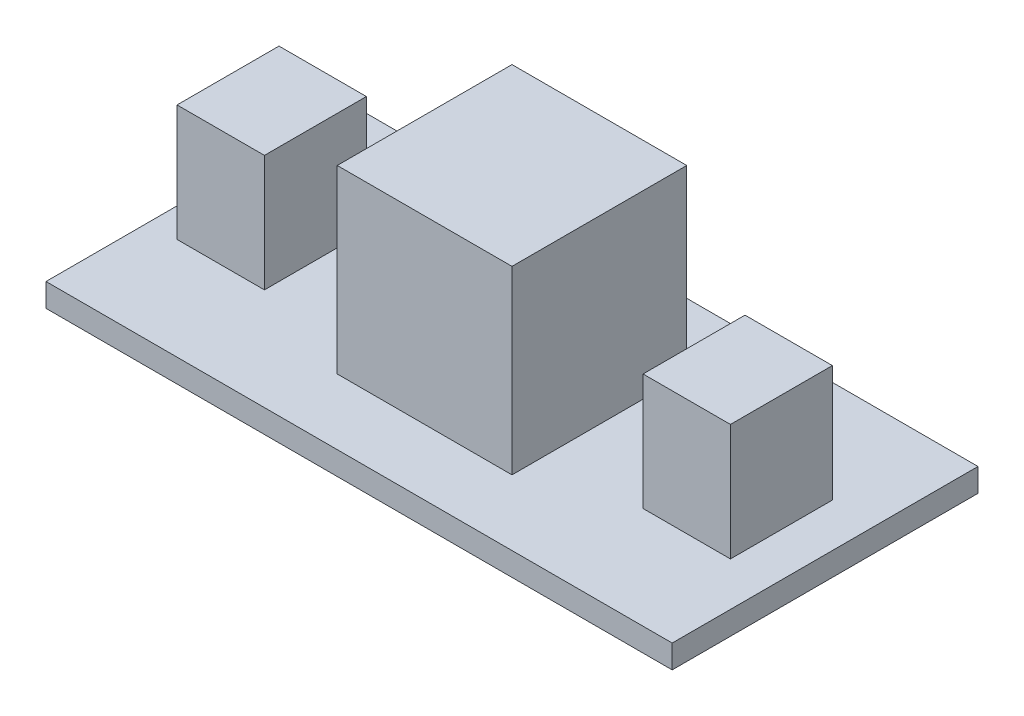
SolidWorks part; units mm, degrees
ref_plane "Front Plane" through (0, 0, 0) normal (0, 0, 1) x (1, 0, 0)
ref_plane "Top Plane" through (0, 0, 0) normal (0, 1, 0) x (1, 0, 0)
ref_plane "Right Plane" through (0, 0, 0) normal (1, 0, 0) x (0, 0, -1)
other "Configuration Table"
sketch "Sketch1" plane through (0, 0, 0) normal (0, 1, 0) x (1, 0, 0)
  line L1 (-21.5, -10.5) -> (21.5, -10.5)
  line L2 (-21.5, -10.5) -> (-21.5, 10.5)
  line L3 (-21.5, 10.5) -> (21.5, 10.5)
  line L4 (21.5, -10.5) -> (21.5, 10.5)
  line L5 (-21.5, -10.5) -> (21.5, 10.5) construction
  line L6 (-21.5, 10.5) -> (21.5, -10.5) construction
  point P6 (0, 0)
  dimension "D1" = 43
  dimension "D2" = 21
extrude "Board" add sketch "Sketch1" along normal blind 1.6
sketch "Sketch2" plane through (0, 0, 0) normal (0, 1, 0) x (1, 0, 0)
  line L0 (-6, -6) -> (6, -6)
  line L1 (6, -6) -> (6, 6)
  line L2 (6, 6) -> (-6, 6)
  line L3 (-6, 6) -> (-6, -6)
extrude "Inductor" add sketch "Sketch2" along normal blind 12.4 from offset 1.6
sketch "Sketch3" plane through (0, 0, 0) normal (0, 1, 0) x (1, 0, 0)
  line L0 (-19.5, -3.5) -> (-13.5, -3.5)
  line L1 (-13.5, -3.5) -> (-13.5, 3.5)
  line L2 (-13.5, 3.5) -> (-19.5, 3.5)
  line L3 (-19.5, 3.5) -> (-19.5, -3.5)
extrude "Input_Cap" add sketch "Sketch3" along normal blind 8 from offset 1.6
sketch "Sketch4" plane through (0, 0, 0) normal (0, 1, 0) x (1, 0, 0)
  line L0 (12.5, -3.5) -> (18.5, -3.5)
  line L1 (18.5, -3.5) -> (18.5, 3.5)
  line L2 (18.5, 3.5) -> (12.5, 3.5)
  line L3 (12.5, 3.5) -> (12.5, -3.5)
extrude "Output_Cap" add sketch "Sketch4" along normal blind 8 from offset 1.6
equation "\"Jar_OD\"= 90  'ASSUMED - Part G fallback - jar outer diameter"
equation "\"Jar_H\"= 120  'ASSUMED - Part G fallback - jar height"
equation "\"Pump_L\"= 45  'ASSUMED - Part G fallback"
equation "\"Pump_W\"= 24  'ASSUMED - Part G fallback"
equation "\"Pump_H\"= 33  'ASSUMED - Part G fallback"
equation "\"Pump_Outlet_OD\"= 7.5  'ASSUMED - Part G fallback"
equation "\"Tube_OD\"= 8  'ASSUMED - Part G fallback"
equation "\"Tube_ID\"= 6  'ASSUMED - Part G fallback"
equation "\"TDS_Body_Dia\"= 12  'ASSUMED - Part G fallback"
equation "\"TDS_Wet_Len\"= 45  'ASSUMED - Part G fallback - length in water"
equation "\"DS_Tube_Dia\"= 6  'ASSUMED - Part G fallback"
equation "\"DS_Tube_Len\"= 50  'ASSUMED - Part G fallback"
equation "\"ORP_Body_Dia\"= 12  'ASSUMED - Part G fallback"
equation "\"ORP_Body_Len\"= 150  'ASSUMED - Part G fallback"
equation "\"ORP_Cap_Dia\"= 16  'ASSUMED - Part G fallback"
equation "\"Turb_W\"= 33  'ASSUMED - Part G fallback - head width"
equation "\"Turb_D\"= 28  'ASSUMED - Part G fallback - head depth"
equation "\"Turb_H\"= 30  'ASSUMED - Part G fallback - head height"
equation "\"Turb_Slot_W\"= 10  'ASSUMED - Part G fallback - slot width"
equation "\"Flow_L\"= 62  'ASSUMED - Part G fallback YF-S201"
equation "\"Flow_W\"= 36  'ASSUMED - Part G fallback"
equation "\"Flow_H\"= 35  'ASSUMED - Part G fallback"
equation "\"Thread_G12_OD\"= 20.955  'ASSUMED - Part G fallback thread G1/2 (major diameter)"
equation "\"Valve_L\"= 75  'ASSUMED - Part G fallback"
equation "\"Valve_W\"= 45  'ASSUMED - Part G fallback"
equation "\"Valve_H\"= 60  'ASSUMED - Part G fallback"
equation "\"Tee_L\"= 40  'ASSUMED - Part G fallback - overall length"
equation "\"Tee_Branch_L\"= 25  'ASSUMED - Part G fallback"
equation "\"Tee_OD\"= 12  'ASSUMED - Part G fallback"
equation "\"LED_Board_L\"= 20  'ASSUMED - Part G fallback"
equation "\"LED_Board_W\"= 20  'ASSUMED - Part G fallback - LED at centre"
equation "\"GUVA_L\"= 20  'ASSUMED - Part G fallback"
equation "\"GUVA_W\"= 12  'ASSUMED - Part G fallback - sensor at centre"
equation "\"Reed_L\"= 27  'ASSUMED - Part G fallback MC-38 half"
equation "\"Reed_W\"= 14  'ASSUMED - Part G fallback"
equation "\"Reed_H\"= 8  'ASSUMED - Part G fallback"
equation "\"ESP_L\"= 51  'ASSUMED - Part G fallback"
equation "\"ESP_W\"= 28  'ASSUMED - Part G fallback"
equation "\"TFT_L\"= 58  'ASSUMED - Part G fallback - board"
equation "\"TFT_W\"= 35  'ASSUMED - Part G fallback - board"
equation "\"TFT_Win_L\"= 35  'ASSUMED - Part G fallback - visible window"
equation "\"TFT_Win_W\"= 28  'ASSUMED - Part G fallback - visible window"
equation "\"Relay_L\"= 50  'ASSUMED - Part G fallback"
equation "\"Relay_W\"= 26  'ASSUMED - Part G fallback"
equation "\"Relay_H\"= 19  'ASSUMED - Part G fallback"
equation "\"Mosfet_L\"= 34  'ASSUMED - Part G fallback"
equation "\"Mosfet_W\"= 17  'ASSUMED - Part G fallback"
equation "\"Mosfet_H\"= 12  'ASSUMED - Part G fallback"
equation "\"TDS_Board_L\"= 42  'ASSUMED - Part G fallback"
equation "\"TDS_Board_W\"= 32  'ASSUMED - Part G fallback"
equation "\"Turb_Board_L\"= 38  'ASSUMED - Part G fallback"
equation "\"Turb_Board_W\"= 28  'ASSUMED - Part G fallback"
equation "\"BNC_Thread_Dia\"= 9.5  'ASSUMED - Part G fallback"
equation "\"Plate_L\"= 420  'ASSUMED - Part G fallback"
equation "\"Plate_W\"= 297  'ASSUMED - Part G fallback"
equation "\"Plate_T\"= 6  'ASSUMED - Part G fallback"
equation "\"Booster_L\"= 150  'ASSUMED - Part G fallback - booster pump"
equation "\"Booster_W\"= 95  'ASSUMED - Part G fallback"
equation "\"Booster_H\"= 100  'ASSUMED - Part G fallback"
equation "\"PTube_OD\"= 6.35  'ASSUMED - Part G fallback - product tube 1/4 inch"
equation "\"Qz_Out\"= 12  'ASSUMED - Part G fallback - quartz channel outside square"
equation "\"Qz_Path\"= 10  'ASSUMED - Part G fallback - quartz channel inside light path"
equation "\"Qz_L\"= 40  'ASSUMED - Part G fallback - quartz channel length"
equation "\"LED860_Dia\"= 5  'ASSUMED - Part G fallback - 860 nm LED"
equation "\"BPW_L\"= 5.4  'ASSUMED - Part G fallback - BPW34"
equation "\"BPW_W\"= 4.3  'ASSUMED - Part G fallback - BPW34"
equation "\"Cart_Dia\"= 50  'ASSUMED - Part G fallback - sediment and pre-carbon cartridges"
equation "\"Cart_L\"= 255  'ASSUMED - Part G fallback"
equation "\"UF_Dia\"= 50  'ASSUMED - Part G fallback - UF cartridge"
equation "\"UF_L\"= 260  'ASSUMED - Part G fallback"
equation "\"RO_Dia\"= 62  'ASSUMED - Part G fallback - RO membrane housing"
equation "\"RO_L\"= 300  'ASSUMED - Part G fallback"
equation "\"UVC_Dia\"= 40  'ASSUMED - Part G fallback - UV-C chamber"
equation "\"UVC_L\"= 300  'ASSUMED - Part G fallback"
equation "\"Tank_W\"= 260  'ASSUMED - Part G fallback - storage tank"
equation "\"Tank_D\"= 160  'ASSUMED - Part G fallback"
equation "\"Tank_H\"= 300  'ASSUMED - Part G fallback"
equation "\"Cab_W\"= 400  'ASSUMED - Part G fallback - purifier cabinet"
equation "\"Cab_D\"= 270  'ASSUMED - Part G fallback"
equation "\"Cab_H\"= 560  'ASSUMED - Part G fallback"
equation "\"ORP_Board_L\"= 40  'ASSUMED - Part G fallback - ORP buffer board"
equation "\"ORP_Board_W\"= 30  'ASSUMED - Part G fallback"
equation "\"Opt_Board_L\"= 50  'ASSUMED - Part G fallback - optical front-end board"
equation "\"Opt_Board_W\"= 40  'ASSUMED - Part G fallback"
equation "\"Buck_L\"= 43  'ASSUMED - Part G fallback - 12 V to 5 V buck module"
equation "\"Buck_W\"= 21  'ASSUMED - Part G fallback"
equation "\"Buck_H\"= 14  'ASSUMED - Part G fallback"
equation "\"BB_L\"= 165  'ASSUMED - Part G fallback - breadboard (As_Built_R3 only)"
equation "\"BB_W\"= 55  'ASSUMED - Part G fallback"
equation "\"BB_H\"= 10  'ASSUMED - Part G fallback"
equation "\"Cuv_W\"= 12.5  'ASSUMED - old R3 cuvette (station suppressed in SS4)"
equation "\"Cuv_D\"= 12.5  'ASSUMED - old R3 cuvette (station suppressed in SS4)"
equation "\"Cuv_H\"= 45  'ASSUMED - old R3 cuvette (station suppressed in SS4)"
equation "\"Probe_Clr\"= 0.3  'DESIGN VALUE - Part C rule 3 - printed probe hole = diameter + 0.3"
equation "\"Label_H\"= 0.6  'DESIGN VALUE - Part D - raised label height"
equation "\"D1@Sketch1\" = \"Buck_L\""
equation "\"D2@Sketch1\" = \"Buck_W\""
